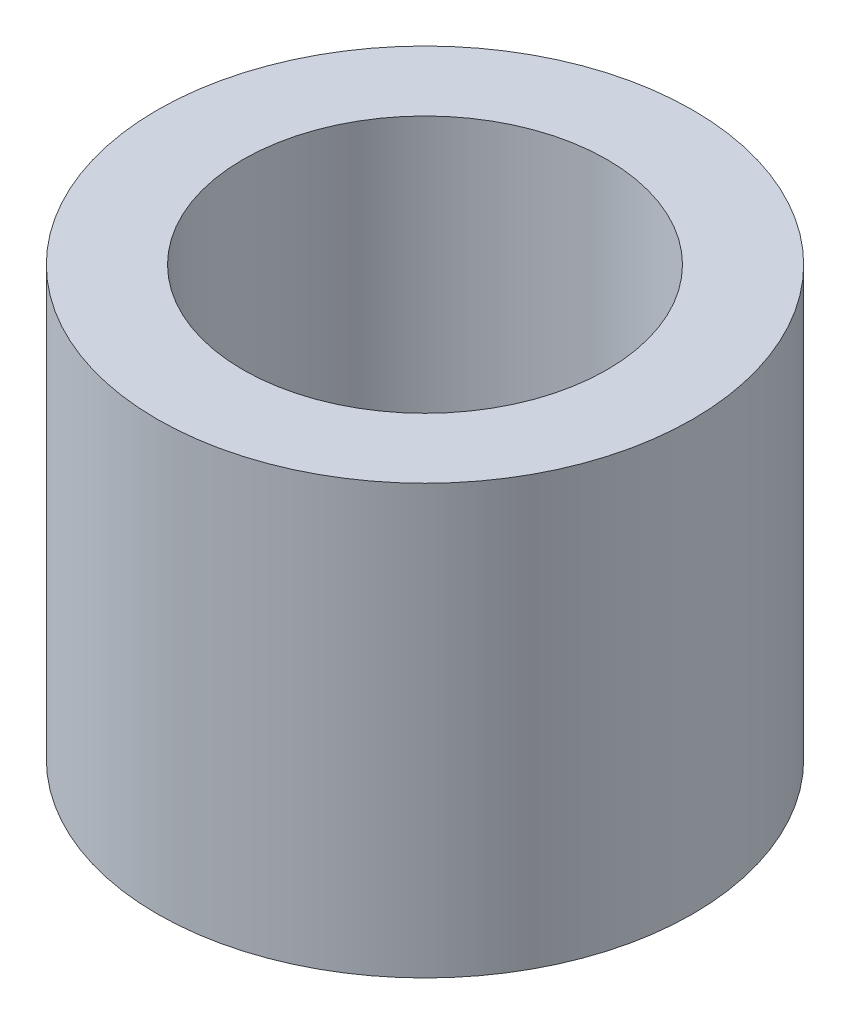
SolidWorks part; units mm, degrees
ref_plane "Спереди" through (0, 0, 0) normal (0, 0, 1) x (1, 0, 0)
ref_plane "Сверху" through (0, 0, 0) normal (0, 1, 0) x (1, 0, 0)
ref_plane "Справа" through (0, 0, 0) normal (1, 0, 0) x (0, 0, -1)
sketch "Эскиз1" plane through (0, 0, 0) normal (0, 1, 0) x (1, 0, 0)
  circle A0 centre (0, 0) radius 1.7
  circle A1 centre (0, 0) radius 2.5
  dimension "D1" = 3.4
  dimension "D2" = 5
extrude "Бобышка-Вытянуть1" add sketch "Эскиз1" along normal blind 4
